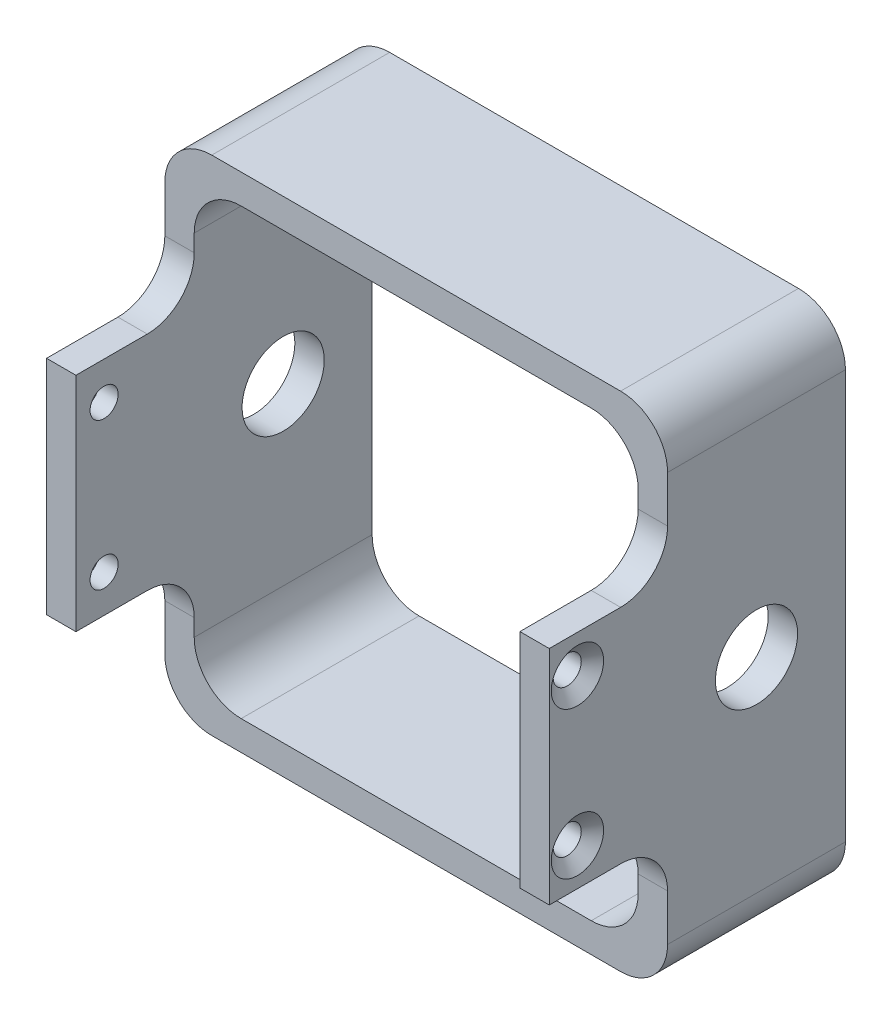
SolidWorks part; units mm, degrees
ref_plane "Front Plane" through (0, 0, 0) normal (0, 0, 1) x (1, 0, 0)
ref_plane "Top Plane" through (0, 0, 0) normal (0, 1, 0) x (1, 0, 0)
ref_plane "Right Plane" through (0, 0, 0) normal (1, 0, 0) x (0, 0, -1)
sketch "Sketch1" plane through (0, 0, 0) normal (0, 0, 1) x (1, 0, 0)
  line L0 (55, 0) -> (-55, 0) construction
  line L1 (-34.0042, -34.0043) -> (34.0043, -34.0043)
  line L2 (-34.0042, -34.0043) -> (-34.0043, 34.0042)
  line L3 (-34.0043, 34.0042) -> (34.0042, 34.0042)
  line L4 (34.0043, -34.0043) -> (34.0042, 34.0042)
  line L5 (-34.0042, -34.0043) -> (34.0042, 34.0042) construction
  line L6 (-34.0043, 34.0042) -> (34.0043, -34.0043) construction
  line L7 (0, -55) -> (0, 55) construction
  line L9 (-30.0292, -30.0292) -> (30.0291, -30.0292)
  line L10 (-30.0292, -30.0292) -> (-30.0292, 30.0291)
  line L11 (-30.0292, 30.0291) -> (30.0291, 30.0291)
  line L12 (30.0291, -30.0292) -> (30.0291, 30.0291)
  line L13 (-30.0292, -30.0292) -> (30.0291, 30.0291) construction
  line L14 (-30.0292, 30.0291) -> (30.0291, -30.0292) construction
  point P0 (0, 0)
  point P10 (0, 0)
  dimension "D1" = 68.0085
  dimension "D2" = 68.0085
  dimension "D3" = 60.0583
  dimension "D4" = 60.0583
extrude "Boss-Extrude1" add sketch "Sketch1" along normal blind 24.0665
sketch "Sketch3" plane through (34.0042, 0, 0) normal (1, 0, 0) x (0, 0, -1)
  line L0 (13.2366, 0) -> (-13.2366, 0) construction
  line L1 (-24.0665, 34.0042) -> (0, 34.0042) construction
  point P0 (-12.0333, 0)
  point P5 (-12.0333, 34.0042)
hole_wizard "7/16 (0.4375) Diameter Hole1" positions "Sketch4" profile "Sketch5" hole size "7/16" standard "ANSI Inch" end condition through all
sketch "Sketch4" plane through (34.0042, 0, 0) normal (1, 0, 0) x (0, 0, -1)
  point P0 (-12.0333, 0)
sketch "Sketch5" plane through (34.0042, 0, 12.0333) normal (0, 1, 0) x (0, 0, -1)
  line L0 (0, 0) -> (0, 68.0085)
  line L1 (0, 68.0085) -> (5.5562, 68.0085)
  line L2 (5.5562, 68.0085) -> (5.5562, 0)
  line L5 (5.5562, 0) -> (0, 0)
  line L11 (0, -6.35) -> (0, 107.95) construction
  dimension "Thru Hole Dia." = 11.1125
  dimension "Thru Hole Depth" = 68.0085
sketch "Sketch10" plane through (-34.0042, 0, 0) normal (-1, 0, 0) x (0, 0, 1)
  line L0 (40.0685, 15.0241) -> (40.0685, -15.0241)
  line L1 (13.2366, 0) -> (-13.2366, 0) construction
  line L2 (24.0665, 34.0042) -> (24.0665, -34.0043) construction
  line L3 (40.0685, 15.0241) -> (24.0665, 15.0241)
  line L4 (24.0665, 15.0241) -> (24.0665, -15.0241)
  line L5 (24.0665, -15.0241) -> (40.0685, -15.0241)
  point P3 (40.0685, 0)
  dimension "D1" = 30.0482
  dimension "D2" = 16.002
extrude "Boss-Extrude2" add sketch "Sketch10" against normal blind 3.9751 contours L5 L0 L3 L4
fillet "Fillet1" radius 6.35 2 edges at (-32.0167, -15.0241, 24.0665) (-32.0167, 15.0241, 24.0665)
mirror "Mirror1" about plane through (0, 0, 0) normal (1, 0, 0) of "Boss-Extrude2", "Fillet1"
fillet "Fillet2" radius 6.35 4 edges at (-34.0042, -34.0043, 12.0333) (34.0043, -34.0043, 12.0333) (-34.0043, 34.0042, 12.0333) (34.0042, 34.0042, 12.0333)
fillet "Fillet3" radius 6.35 4 edges at (-30.0292, -30.0292, 12.0333) (30.0291, -30.0292, 12.0333) (-30.0292, 30.0291, 12.0333) (30.0291, 30.0291, 12.0333)
sketch "Sketch11" plane through (-34.0042, 0, 0) normal (-1, 0, 0) x (0, 0, 1)
  line L0 (40.0685, 15.0241) -> (30.4165, 15.0241) construction
  line L1 (30.4165, -15.0241) -> (40.0685, -15.0241) construction
  line L2 (40.0685, 15.0241) -> (40.0685, -15.0241) construction
  point P0 (36.2585, 9.9441)
  point P1 (36.2585, -9.9441)
  point P8 (0, 0)
  dimension "D1" = 5.08
  dimension "D2" = 5.08
  dimension "D3" = 3.81
hole_wizard "CSK for #6 Flat Head Machine Screw (100)1" positions "Sketch12" profile "Sketch14" countersink size "#6" standard "ANSI Inch"
sketch "Sketch12" plane through (-34.0042, 0, 0) normal (-1, 0, 0) x (0, 0, 1)
  point P0 (36.2585, 9.9441)
  point P3 (36.2585, -9.9441)
sketch "Sketch14" plane through (-34.0042, 9.9441, 36.2585) normal (0, 1, 0) x (0, 0, 1)
  line L0 (0, 0) -> (0, 10.5388)
  line L1 (0, 10.5388) -> (1.8986, 9.398)
  line L2 (1.8986, 9.398) -> (1.8986, 1.38)
  line L3 (1.8986, 1.38) -> (3.5433, 0)
  line L5 (3.5433, 0) -> (0, 0)
  line L6 (-1.8986, 1.38) -> (-3.5433, 0) construction
  line L10 (0, 10.5388) -> (-1.8987, 9.398) construction
  line L11 (0, -6.35) -> (0, 107.95) construction
  dimension "Hole Dia." = 3.7973
  dimension "Hole Depth" = 9.398
  dimension "Near C'Sink Dia." = 7.0866
  dimension "Near C'Sink Angle" = 100
  dimension "Drill Angle" = 118
mirror "Mirror2" about plane through (0, 0, 0) normal (1, 0, 0) of "CSK for #6 Flat Head Machine Screw (100)1"
